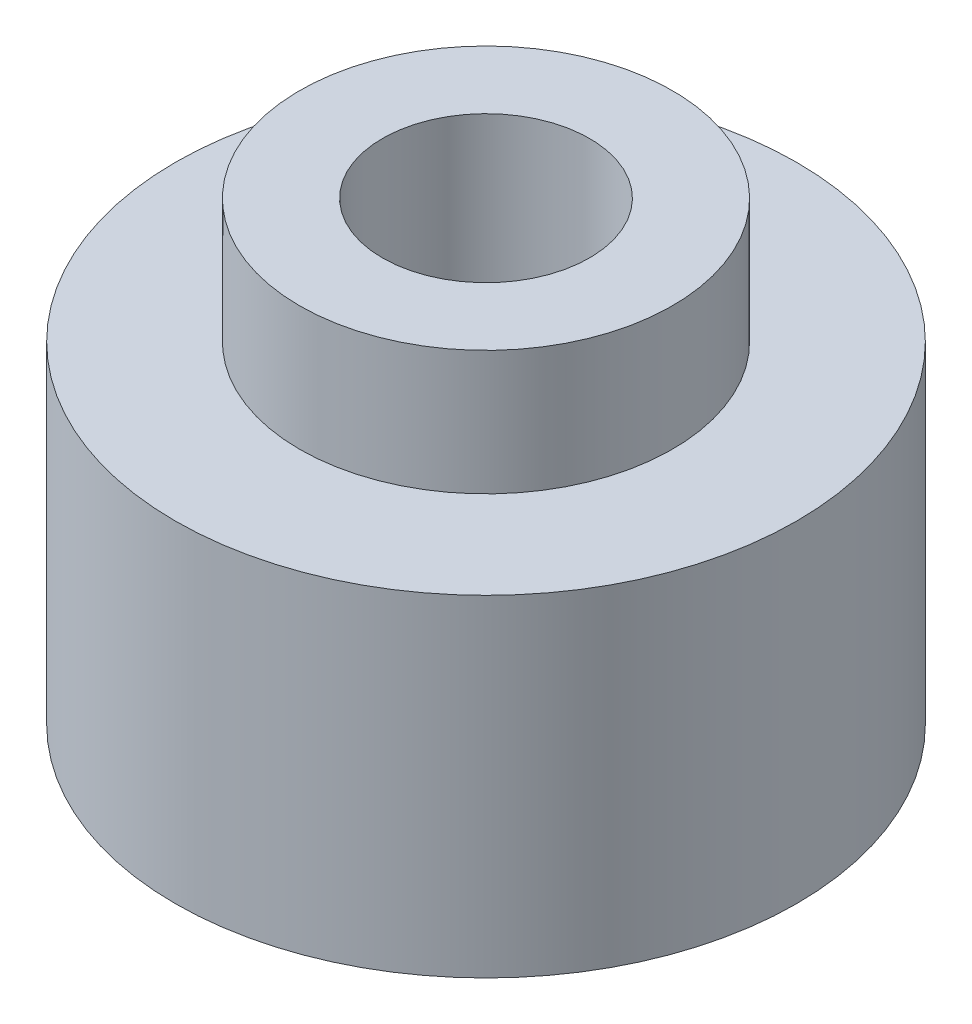
SolidWorks part; units mm, degrees
ref_plane "Front Plane" through (0, 0, 0) normal (0, 0, 1) x (1, 0, 0)
ref_plane "Top Plane" through (0, 0, 0) normal (0, 1, 0) x (1, 0, 0)
ref_plane "Right Plane" through (0, 0, 0) normal (1, 0, 0) x (0, 0, -1)
sketch "Sketch1" plane through (0, 0, 0) normal (0, 1, 0) x (1, 0, 0)
  circle A0 centre (0, 0) radius 7.5
  dimension "D1" = 15
extrude "Boss-Extrude1" add sketch "Sketch1" along normal blind 11
sketch "Sketch2" plane through (0, 11, 0) normal (0, 1, 0) x (1, 0, 0)
  circle A0 centre (0, 0) radius 2.5
  dimension "D1" = 5
extrude "Cut-Extrude1" cut sketch "Sketch2" against normal through all
sketch "Sketch3" plane through (0, 11, 0) normal (0, 1, 0) x (1, 0, 0)
  circle A0 centre (0, 0) radius 7.5
  circle A2 centre (0, 0) radius 4.5
  dimension "D1" = 9
extrude "Cut-Extrude3" cut sketch "Sketch3" against normal blind 3
